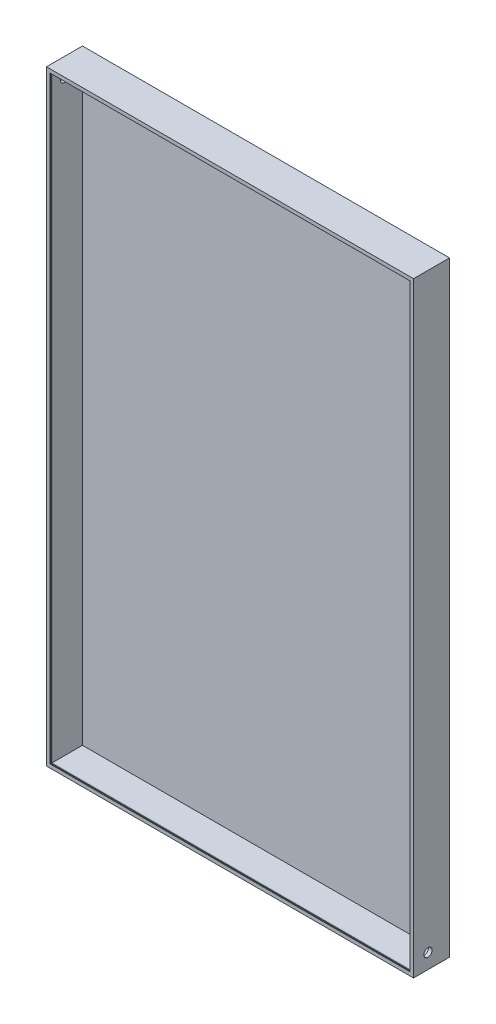
SolidWorks part; units mm, degrees
material "1060 Alloy"
ref_plane "Front Plane" through (0, 0, 0) normal (0, 0, 1) x (1, 0, 0)
ref_plane "Top Plane" through (0, 0, 0) normal (0, 1, 0) x (1, 0, 0)
ref_plane "Right Plane" through (0, 0, 0) normal (1, 0, 0) x (0, 0, -1)
sketch "Sketch1" plane through (0, 0, 0) normal (0, 0, 1) x (1, 0, 0)
  line L0 (0, 0) -> (0, 1662.9)
  line L1 (0, 0) -> (1000, 0)
  line L2 (1000, 0) -> (1000, 1662.9)
  line L3 (1000, 1662.9) -> (0, 1662.9)
  dimension "D1" = 1662.9
  dimension "D2" = 1000
extrude "Boss-Extrude1" add sketch "Sketch1" along normal blind 10
sketch "Sketch2" plane through (0, 0, 0) normal (0, 0, 1) x (1, 0, 0)
  line L0 (0, 1662.9) -> (1000, 1662.9)
  line L1 (1000, 1662.9) -> (1000, 0)
  line L2 (1000, 0) -> (0, 0)
  line L3 (0, 0) -> (0, 1662.9)
  line L4 (-10, 1672.9) -> (1010, 1672.9)
  line L5 (1010, 1672.9) -> (1010, -10)
  line L6 (1010, -10) -> (-10, -10)
  line L7 (-10, -10) -> (-10, 1672.9)
  dimension "D1" = 10
  dimension "D2" = 10
  dimension "D3" = 10
  dimension "D4" = 10
extrude "Boss-Extrude2" add sketch "Sketch2" along normal blind 100
sketch "Sketch3" plane through (-10, 0, 0) normal (-1, 0, 0) x (0, 0, 1)
  line L0 (100, 1672.9) -> (100, -10) construction
  line L1 (100, 1672.9) -> (0, 1672.9) construction
  circle A0 centre (60, 1631.45) radius 11.45
  dimension "D3" = 22.9
  dimension "D1" = 40
  dimension "D2" = 41.45
extrude "Cut-Extrude1" cut sketch "Sketch3" against normal up to next
sketch "Sketch4" plane through (1010, 0, 0) normal (1, 0, 0) x (0, 0, -1)
  line L0 (-100, -10) -> (-100, 1672.9) construction
  line L1 (-100, -10) -> (0, -10) construction
  circle A0 centre (-60, 31.47) radius 11.45
  dimension "D1" = 22.9
  dimension "D2" = 40
  dimension "D3" = 41.47
extrude "Cut-Extrude2" cut sketch "Sketch4" against normal blind 10
ref_plane "Plane1" through (0, 0, 98) normal (0, 0, 1) x (1, 0, 0)
sketch "Sketch6" plane through (0, 0, 98) normal (0, 0, 1) x (1, 0, 0)
  line L1 (0, 1662.9) -> (1000, 1662.9)
  line L2 (0, 1662.9) -> (0, 0)
  line L3 (0, 0) -> (1000, 0)
  line L4 (1000, 1662.9) -> (1000, 0)
  line L5 (2, 1660.9) -> (998, 1660.9)
  line L6 (2, 1660.9) -> (2, 2)
  line L7 (2, 2) -> (998, 2)
  line L8 (998, 1660.9) -> (998, 2)
  dimension "D1" = 2
  dimension "D2" = 2
  dimension "D3" = 2
  dimension "D4" = 2
extrude "Boss-Extrude4" add sketch "Sketch6" against normal blind 2
